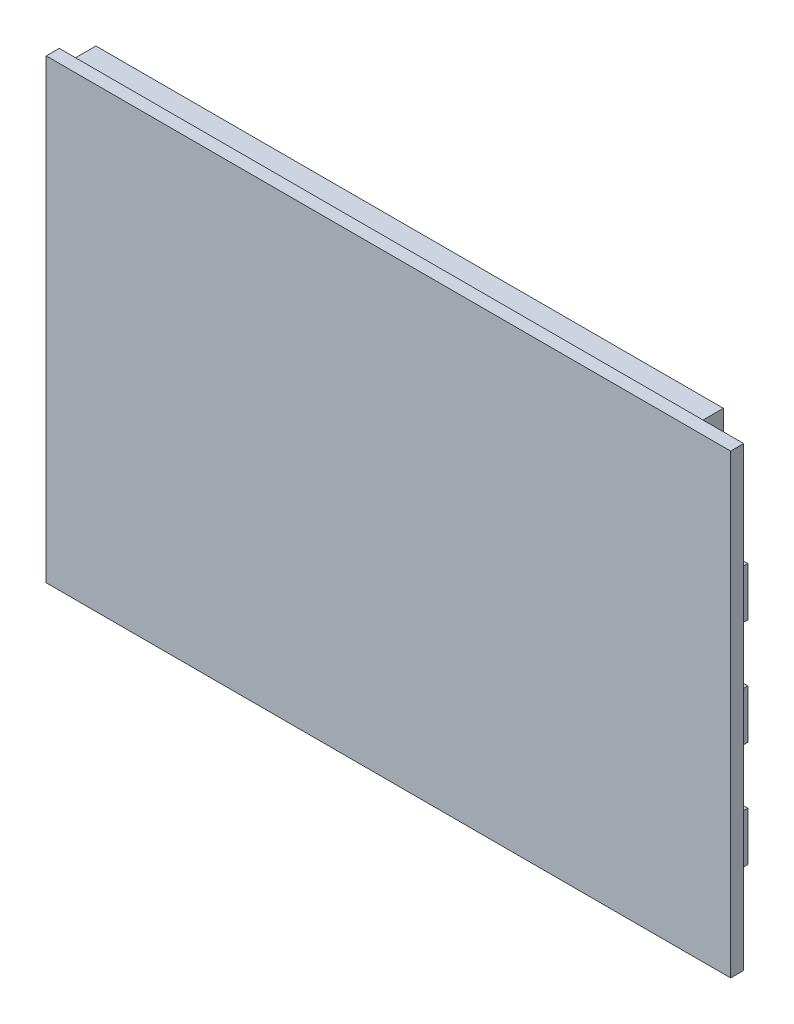
SolidWorks part; units mm, degrees
ref_plane "Plan de face" through (0, 0, 0) normal (0, 0, 1) x (1, 0, 0)
ref_plane "Plan de dessus" through (0, 0, 0) normal (0, 1, 0) x (1, 0, 0)
ref_plane "Plan de droite" through (0, 0, 0) normal (1, 0, 0) x (0, 0, -1)
sketch "Esquisse5" plane through (0, 0, 0) normal (0, 0, 1) x (1, 0, 0)
  line L1 (0, 0) -> (84, 0)
  line L2 (0, 0) -> (0, 56)
  line L3 (0, 56) -> (84, 56)
  line L4 (84, 0) -> (84, 56)
  dimension "D1" = 84
  dimension "D2" = 56
extrude "Boss.-Extru.6" add sketch "Esquisse5" along normal blind 1.6 contours L2 L1 L4 L3
sketch "Esquisse6" plane through (0, 0, 0) normal (0, 0, -1) x (-1, 0, 0)
  line L0 (-84, 0) -> (-84, 56) construction
  line L1 (-78, 55) -> (-1, 55)
  line L2 (-78, 55) -> (-78, 1)
  line L3 (-78, 1) -> (-1, 1)
  line L4 (-1, 55) -> (-1, 1)
  line L5 (0, 56) -> (-84, 56) construction
  dimension "D1" = 77
  dimension "D2" = 54
  dimension "D3" = 6
  dimension "D4" = 1
extrude "Boss.-Extru.8" add sketch "Esquisse6" along normal blind 3.5
sketch "Esquisse7" plane through (0, 0, 0) normal (0, 0, -1) x (-1, 0, 0)
  line L0 (-84, 0) -> (-84, 56) construction
  line L1 (-79, 36) -> (-83, 36)
  line L2 (-79, 36) -> (-79, 42)
  line L3 (-79, 42) -> (-83, 42)
  line L4 (-83, 36) -> (-83, 42)
  line L5 (0, 56) -> (-84, 56) construction
  dimension "D1" = 4
  dimension "D2" = 6
  dimension "D3" = 1
  dimension "D4" = 14
sketch "Esquisse8" plane through (0, 0, 0) normal (0, 0, -1) x (-1, 0, 0)
  line L2 (0, 56) -> (-84, 56) construction
  line L3 (-83, 29) -> (-79, 29)
  line L4 (-83, 29) -> (-83, 23)
  line L5 (-83, 23) -> (-79, 23)
  line L6 (-79, 29) -> (-79, 23)
  line L11 (-84, 0) -> (-84, 56) construction
  point P12 (0, 0)
  point P13 (0, 0)
  dimension "D1" = 4
  dimension "D4" = 6
  dimension "D5" = 27
  dimension "D8" = 1
extrude "Boss.-Extru.10" add sketch "Esquisse8" along normal blind 1.5 contours L5 L6 L3 L4
extrude "Boss.-Extru.11" add sketch "Esquisse7" along normal blind 1.5
sketch "Esquisse11" plane through (0, 0, 0) normal (0, 0, -1) x (-1, 0, 0)
  line L0 (-84, 0) -> (-84, 56) construction
  line L1 (-83, 10) -> (-79, 10)
  line L2 (-83, 10) -> (-83, 16)
  line L3 (-83, 16) -> (-79, 16)
  line L4 (-79, 10) -> (-79, 16)
  line L5 (0, 56) -> (-84, 56) construction
  dimension "D1" = 4
  dimension "D2" = 6
  dimension "D3" = 1
  dimension "D4" = 40
extrude "Boss.-Extru.12" add sketch "Esquisse11" along normal blind 1.5
